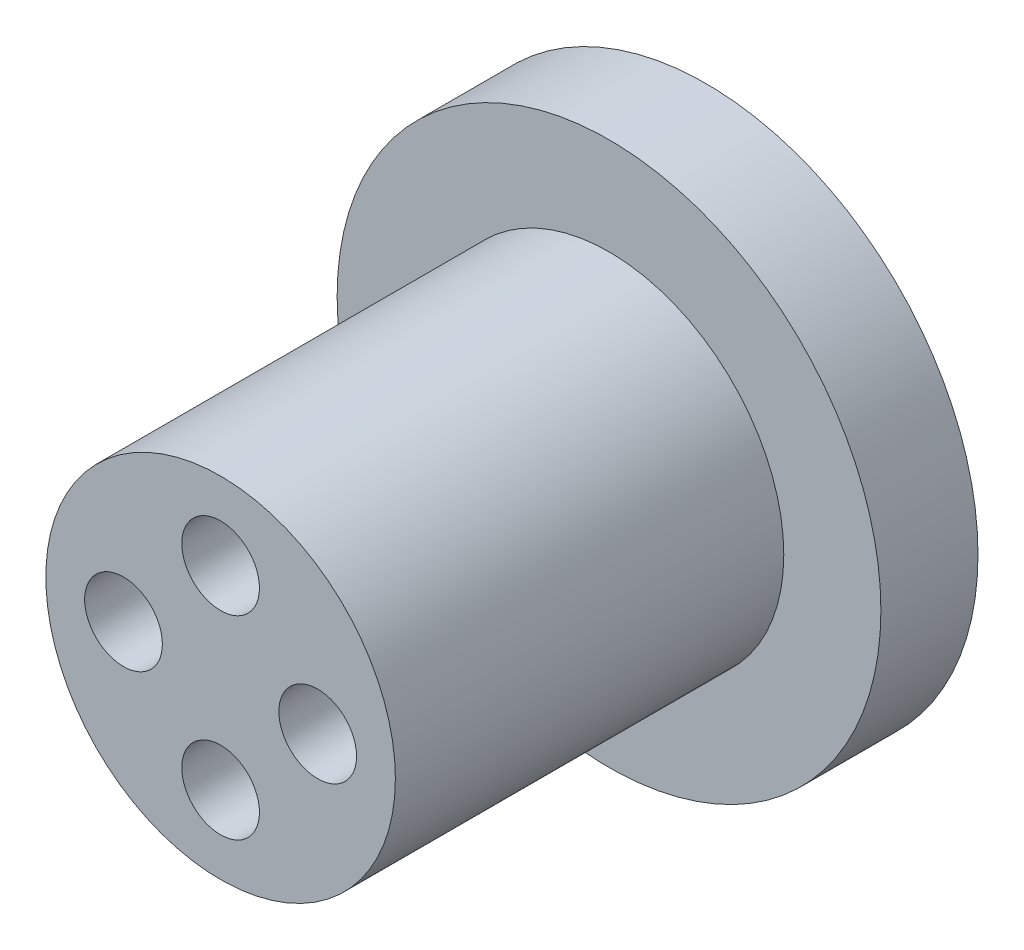
SolidWorks part; units mm, degrees
ref_plane "前视基准面" through (0, 0, 0) normal (0, 0, 1) x (1, 0, 0)
ref_plane "上视基准面" through (0, 0, 0) normal (0, 1, 0) x (1, 0, 0)
ref_plane "右视基准面" through (0, 0, 0) normal (1, 0, 0) x (0, 0, -1)
other "Configuration Table"
sketch "Sketch1" plane through (0, 0, 0) normal (0, 0, 1) x (1, 0, 0)
  circle A0 centre (0, 0) radius 7
  dimension "D1" = 14
extrude "Boss-Extrude1" add sketch "Sketch1" along normal blind 2.5
sketch "Sketch2" plane through (0, 0, 2.5) normal (0, 0, 1) x (1, 0, 0)
  circle A0 centre (0, 0) radius 4.5
  dimension "D1" = 9
extrude "Boss-Extrude2" add sketch "Sketch2" along normal blind 10
sketch "Sketch3" plane through (0, 0, 12.5) normal (0, 0, 1) x (1, 0, 0)
  circle A0 centre (0, 0) radius 2.5 construction
  circle A1 centre (0, 2.5) radius 1
  circle A2 centre (2.5, 0) radius 1
  circle A3 centre (0, -2.5) radius 1
  circle A4 centre (-2.5, 0) radius 1
  point P14 (0, 0)
  dimension "D1" = 5
  dimension "D2" = 2
extrude "Cut-Extrude1" cut sketch "Sketch3" against normal blind 5
